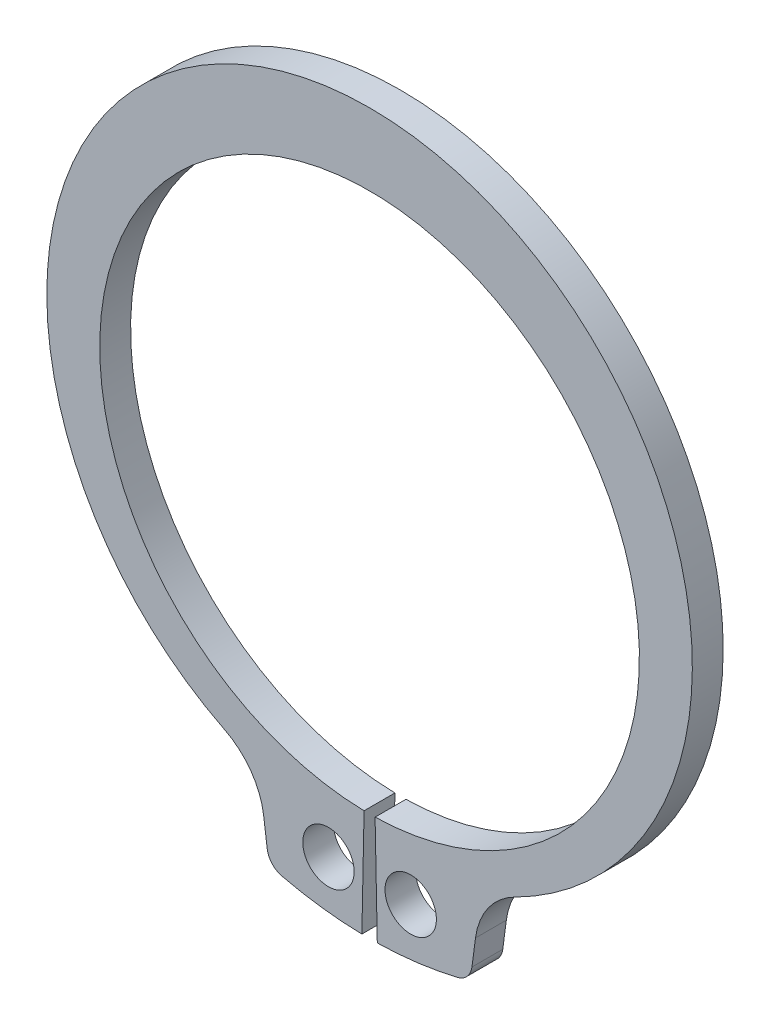
SolidWorks part; units mm, degrees
ref_plane "Plane1" through (0, 0, 0) normal (0, 0, 1) x (1, 0, 0)
ref_plane "Plane2" through (0, 0, 0) normal (0, 1, 0) x (1, 0, 0)
ref_plane "Plane3" through (0, 0, 0) normal (1, 0, 0) x (0, 0, -1)
sketch "Clipboard" plane through (0, 0, 0) normal (0, 0, 1) x (1, 0, 0)
  line L0 (0, 0) -> (2.8, 0)
  line L1 (0, 0) -> (0, 1.4)
  line L2 (0, 0) -> (0, -4.2)
  circle A0 centre (0, 0) radius 1
  circle A1 centre (0, 0) radius 11
  dimension "HoleDia" = 2
  dimension "ShaftDia" = 22
  dimension "LargeSection" = 2.8
  dimension "SmallSection" = 1.4
  dimension "LugSection" = 4.2
sketch "BodySke" plane through (0, 0, 0) normal (0, 0, 1) x (1, 0, 0)
  line L0 (-1.5431, 0) -> (1.5431, 0) construction
  line L1 (0, 0) -> (0, 13.3) construction
  line L2 (0.2143, -10.4978) -> (0.3, -14.6969)
  line L3 (-0.2143, -10.4978) -> (-0.3, -14.6969)
  line L4 (0, 0) -> (6.8966, -12.9818) construction
  line L5 (0, 0) -> (-6.8966, -12.9818) construction
  line L7 (4.1214, -12.6164) -> (3.9832, -13.6665)
  line L8 (-4.1214, -12.6164) -> (-3.9832, -13.6665)
  circle A0 centre (0, 0) radius 10.5 construction
  arc A1 (0.2143, -10.4978) -> (-0.2143, -10.4978) centre (0, 0) ccw
  arc A2 (5.583, -10.5091) -> (-5.583, -10.5091) centre (0, 0.7409) ccw construction
  arc A3 (0.3, -14.6969) -> (3.4138, -14.2981) centre (0, 0) ccw
  arc A4 (5.6397, -10.4808) -> (4.1214, -12.6164) centre (6.8966, -12.9818) ccw
  arc A5 (-4.1214, -12.6164) -> (-5.6397, -10.4808) centre (-6.8966, -12.9818) ccw
  arc A6 (-3.4138, -14.2981) -> (-0.3, -14.6969) centre (0, 0) ccw
  arc A7 (5.6397, -10.4808) -> (-5.6397, -10.4808) centre (0, 0.7409) ccw
  arc A8 (-4.1828, -12.1502) -> (4.1828, -12.1502) centre (0, 0) ccw construction
  circle A9 centre (1.6, -12.75) radius 1
  circle A10 centre (-1.6, -12.75) radius 1
  arc A11 (3.9832, -13.6665) -> (3.4138, -14.2981) centre (3.2396, -13.5686) cw
  arc A12 (-3.9832, -13.6665) -> (-3.4138, -14.2981) centre (-3.2396, -13.5686) ccw
  point P28 (3.9171, -14.1685)
  point P31 (-3.9171, -14.1685)
  dimension "HoleDia" = 2
  dimension "GrooveDia" = 21
  dimension "LugRad" = 14.7
  dimension "HoleOffsetRad" = 12.85
  dimension "D3" = 0.75
  dimension "LargeRad" = 13.3
  dimension "SmallRad" = 11.9
  dimension "SmallAngle" = 55.959
  dimension "D2" = 15
  dimension "HoleSpacing" = 3.2
  dimension "Gap" = 0.6
extrude "Body" add sketch "BodySke" against normal blind 1.2
sketch "NotSke" plane through (0, 0, 0) normal (0, 0, 1) x (1, 0, 0)
  line L0 (1.6, -11.75) -> (1.6, -13.75)
  line L1 (1.6, -13.75) -> (-1.6, -13.75)
  line L2 (-1.6, -13.75) -> (-1.6, -11.75)
  line L3 (-1.6, -11.75) -> (1.6, -11.75)
  circle A0 centre (1.6, -12.75) radius 1 construction
  circle A1 centre (-1.6, -12.75) radius 1 construction
extrude "Notch" [suppressed] cut sketch "NotSke" against normal through all
sketch "UnlSke" plane through (0, 0, 0) normal (0, 0, 1) x (1, 0, 0)
  line L0 (-2.9599, -14.3989) -> (-2.1142, -10.285)
  line L1 (2.9599, -14.3989) -> (2.1142, -10.285)
  arc A0 (2.1142, -10.285) -> (-2.1142, -10.285) centre (0, 0) ccw
  arc A1 (2.9599, -14.3989) -> (-2.9599, -14.3989) centre (0, 0) ccw
  arc A2 (0.3, -14.6969) -> (3.4138, -14.2981) centre (0, 0) ccw construction
  arc A3 (0.2143, -10.4978) -> (-0.2143, -10.4978) centre (0, 0) ccw construction
  circle A4 centre (-1.6, -12.75) radius 1 construction
  circle A5 centre (1.6, -12.75) radius 1 construction
extrude "Unlug" [suppressed] add sketch "UnlSke" against normal through all
equation "' \"ShaftDia@Clipboard\" = 3"
equation "' \"Thickness@Body\" = 0.4"
equation "' \"GrooveDia@BodySke\" = 2.8"
equation "' \"LugSection@Clipboard\" = 1.9"
equation "' \"LargeSection@Clipboard\" = 0.8"
equation "' \"HoleDia@Clipboard\" = 1.0"
equation "' \"ShaftDia@Clipboard\" = 10"
equation "' \"Thickness@Body\" = 1.0"
equation "' \"GrooveDia@BodySke\" = 9.6"
equation "' \"LugSection@Clipboard\" = 3.3"
equation "' \"LargeSection@Clipboard\" = 1.8"
equation "' \"HoleDia@Clipboard\" = 1.5"
equation "\"SmallSection@Clipboard\" = \"LargeSection@Clipboard\" * 0.5"
equation "\"Gap@BodySke\" =  \"Thickness@Body\" / 2"
equation "\"LargeRad@BodySke\" =  \"GrooveDia@BodySke\" / 2 +  \"LargeSection@Clipboard\""
equation "\"SmallRad@BodySke\" =  \"GrooveDia@BodySke\" / 2 +  \"SmallSection@Clipboard\""
equation "\"LugRad@BodySke\" = \"GrooveDia@BodySke\" / 2 + \"LugSection@Clipboard\""
equation "\"HoleOffsetRad@BodySke\" = (  \"ShaftDia@Clipboard\" / 2 + \"LugRad@BodySke\" ) / 2"
equation "\"HoleSpacing@BodySke\" = \"Gap@BodySke\"  * 2 +  \"HoleDia@Clipboard\""
equation "\"HoleDia@BodySke\" =  \"HoleDia@Clipboard\""
equation "\"SmallAngle@BodySke\" = atn(\"HoleSpacing@BodySke\" / 2 / sqr(\"HoleOffsetRad@BodySke\"  * \"HoleOffsetRad@BodySke\" - (\"HoleSpacing@BodySke\" / 2) * (\"HoleSpacing@BodySke\" / 2) ))  * 7 *  (\"LargeRad@BodySke\" / \"SmallRad@BodySke\")* ( 180 / 3.141593)"
